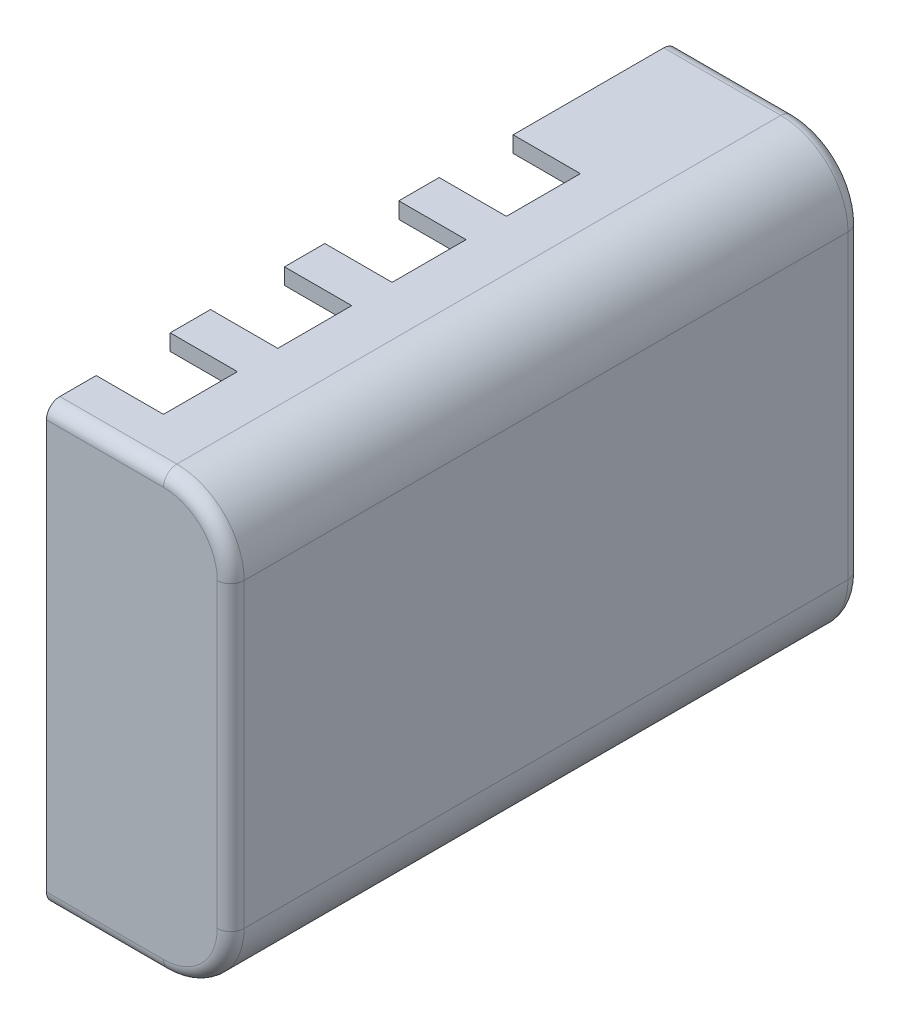
SolidWorks part; units mm, degrees
ref_plane "Front Plane" through (0, 0, 0) normal (0, 0, 1) x (1, 0, 0)
ref_plane "Top Plane" through (0, 0, 0) normal (0, 1, 0) x (1, 0, 0)
ref_plane "Right Plane" through (0, 0, 0) normal (1, 0, 0) x (0, 0, -1)
sketch "Sketch1" plane through (0, 0, 0) normal (1, 0, 0) x (0, 0, -1)
  line L1 (-22.25, -15) -> (22.25, -15)
  line L2 (-22.25, -15) -> (-22.25, 15)
  line L3 (-22.25, 15) -> (22.25, 15)
  line L4 (22.25, -15) -> (22.25, 15)
  line L5 (-22.25, -15) -> (22.25, 15) construction
  line L6 (-22.25, 15) -> (22.25, -15) construction
  point P0 (0, 0)
  dimension "D1" = 44.5
  dimension "D2" = 30
extrude "Boss-Extrude1" add sketch "Sketch1" along normal blind 12.5
shell "Shell2" thickness 1.2
sketch "Sketch2" plane through (0, 15, 0) normal (0, -1, 0) x (1, 0, 0)
  line L0 (0, 19.75) -> (0, 14.25)
  line L1 (0, 19.75) -> (5, 19.75)
  line L2 (0, 14.25) -> (5, 14.25)
  line L3 (5, 19.75) -> (5, 14.25)
  line L4 (0, -22.25) -> (0, 22.25) construction
  line L5 (0, 11.25) -> (0, 5.75)
  line L6 (0, 11.25) -> (5, 11.25)
  line L7 (0, 5.75) -> (5, 5.75)
  line L8 (5, 11.25) -> (5, 5.75)
  line L10 (0, -23.45) -> (0, 23.45) construction
  line L11 (0, 2.75) -> (5, 2.75)
  line L12 (0, 2.75) -> (0, -2.75)
  line L13 (5, 2.75) -> (5, -2.75)
  line L14 (0, -2.75) -> (5, -2.75)
  line L15 (0, -5.75) -> (5, -5.75)
  line L16 (0, -5.75) -> (0, -11.25)
  line L17 (5, -5.75) -> (5, -11.25)
  line L18 (0, -11.25) -> (5, -11.25)
  dimension "D1" = 2.5
  dimension "D2" = 5.5
  dimension "D3" = 5
  dimension "D4" = 3
  dimension "D5" = 5.5
  dimension "D6" = 3
  dimension "D7" = 5.5
  dimension "D8" = 5.5
  dimension "D9" = 3
extrude "Cut-Extrude1" cut sketch "Sketch2" against normal up to surface (1.2 mm away) up to face at (6.85, 16.2, 0)
sketch "Sketch3" plane through (0, 0, -23.45) normal (0, 0, -1) x (-1, 0, 0)
  line L0 (0, -16.2) -> (0, 16.2) construction
  line L1 (0, 3) -> (-1.95, 3)
  line L2 (0, 3) -> (0, -1.5)
  line L3 (0, -1.5) -> (-1.95, -1.5)
  line L4 (-12.5, 15) -> (0, 15) construction
  line L5 (-12.5, 15) -> (0, 15) construction
  line L7 (0, 12) -> (-4.2, 12)
  line L8 (0, 12) -> (0, 7)
  line L9 (0, 7) -> (-4.2, 7)
  line L10 (-4.2, 12) -> (-4.2, 7)
  arc A0 (-1.95, -1.5) -> (-1.95, 3) centre (-1.95, 0.75) cw
  point P7 (-4.2, 0.75)
  dimension "D1" = 4.2
  dimension "D2" = 4.5
  dimension "D3" = 12
  dimension "D4" = 4.2
  dimension "D5" = 5
  dimension "D6" = 3
extrude "Cut-Extrude2" cut sketch "Sketch3" against normal up to surface (1.2 mm away) up to face at (6.25, 0, -22.25)
fillet "Fillet1" radius 5 4 edges at (13.7, 16.2, 0) (12.5, -15, 0) (13.7, -16.2, 0) (12.5, 15, 0)
fillet "Fillet3" radius 1 10 edges at (4.35, -16.2, -23.45) (12.2355, -14.7355, -23.45) (13.7, 0, -23.45) (12.2355, 14.7355, -23.45) (4.35, 16.2, -23.45) (4.35, -16.2, 23.45) (12.2355, -14.7355, 23.45) (13.7, 0, 23.45) (12.2355, 14.7355, 23.45) (4.35, 16.2, 23.45)
